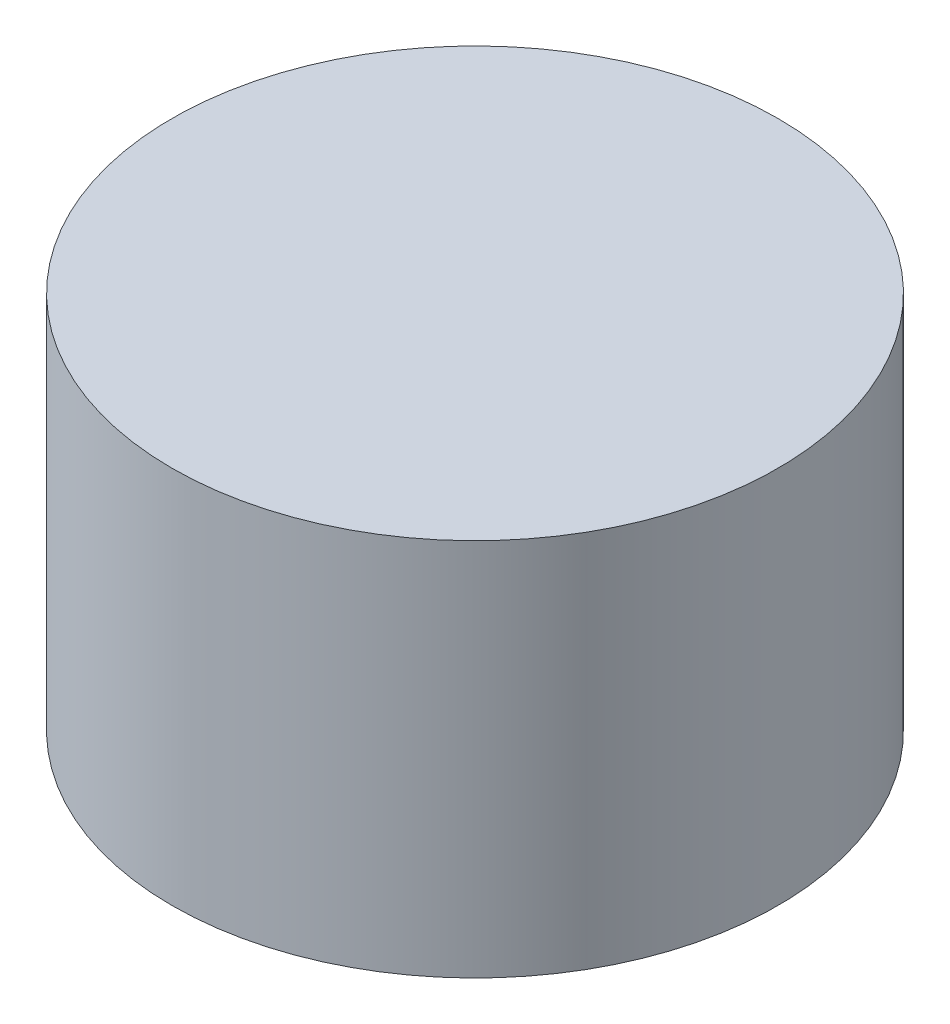
SolidWorks part; units mm, degrees
ref_plane "Front Plane" through (0, 0, 0) normal (0, 0, 1) x (1, 0, 0)
ref_plane "Top Plane" through (0, 0, 0) normal (0, 1, 0) x (1, 0, 0)
ref_plane "Right Plane" through (0, 0, 0) normal (1, 0, 0) x (0, 0, -1)
sketch "Sketch1" plane through (0, 0, 0) normal (0, 1, 0) x (1, 0, 0)
  circle A0 centre (0, 0) radius 20.32
  dimension "D1" = 40.64
extrude "Boss-Extrude1" add sketch "Sketch1" along normal blind 25.4
